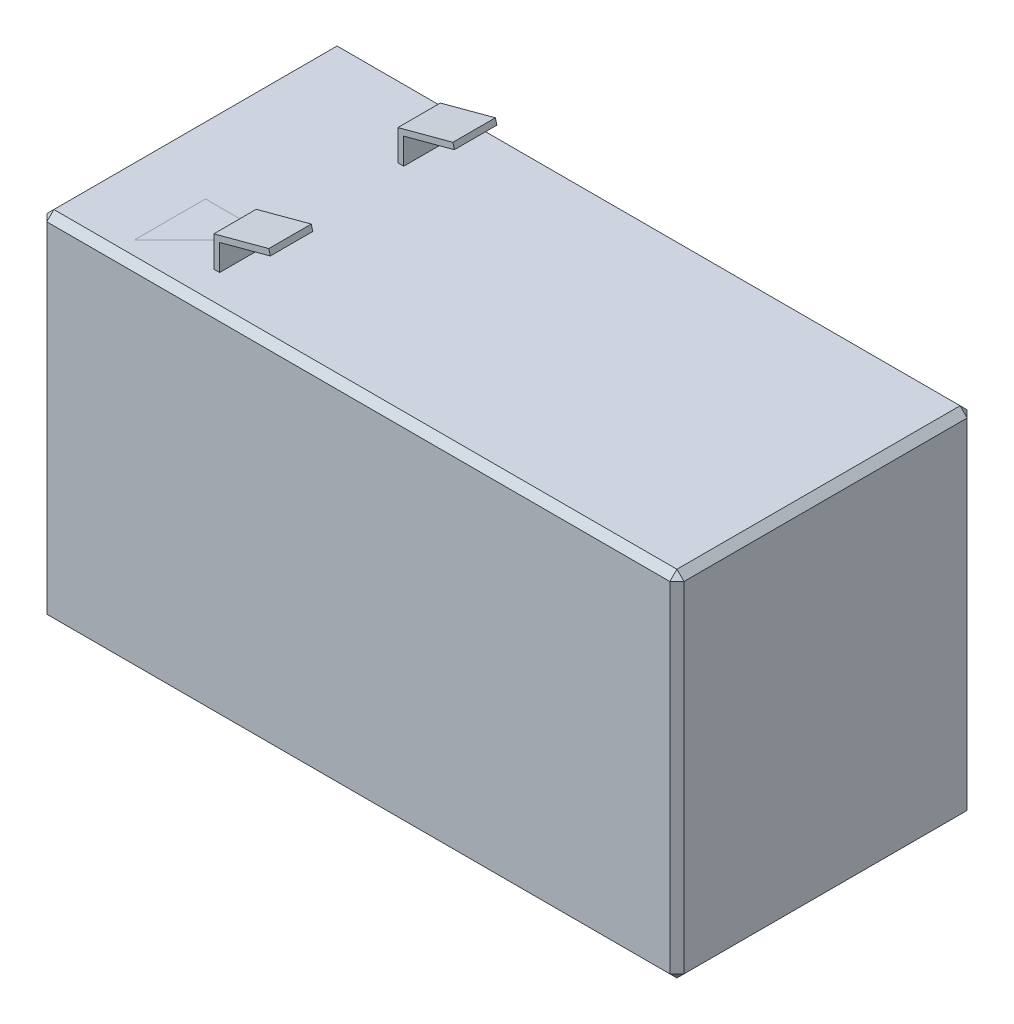
SolidWorks part; units mm, degrees
ref_plane "Plan de face" through (0, 0, 0) normal (0, 0, 1) x (1, 0, 0)
ref_plane "Plan de dessus" through (0, 0, 0) normal (0, 1, 0) x (1, 0, 0)
ref_plane "Plan de droite" through (0, 0, 0) normal (1, 0, 0) x (0, 0, -1)
sketch "Esquisse2" plane through (0, 0, 0) normal (0, 1, 0) x (1, 0, 0)
  line L1 (-45, -21) -> (45, -21)
  line L2 (-45, -21) -> (-45, 21)
  line L3 (-45, 21) -> (45, 21)
  line L4 (45, -21) -> (45, 21)
  line L5 (-45, -21) -> (45, 21) construction
  line L6 (-45, 21) -> (45, -21) construction
  point P0 (0, 0)
  dimension "D1" = 90
  dimension "D2" = 42
extrude "Boss.-Extru.1" add sketch "Esquisse2" along normal blind 50
ref_plane "Plan1" through (0, 0, 13) normal (0, 0, 1) x (1, 0, 0)
chamfer "Chanfrein1" distance 1 angle 45 12 edges at (-45, 0, 0) (-45, 50, 0) (45, 50, 0) (45, 25, -21) (0, 50, -21) (-45, 25, -21) (0, 0, -21) (45, 0, 0) (-45, 25, 21) (0, 50, 21) (45, 25, 21) (0, 0, 21)
sketch "Esquisse5" plane through (0, 0, 13) normal (0, 0, 1) x (1, 0, 0)
  line L0 (-25, 50) -> (-25, 54)
  line L1 (-44, 50) -> (44, 50) construction
  line L2 (-25, 54) -> (-17.5359, 56)
  line L3 (44, 0) -> (-44, 0) construction
  line L4 (-45, 1) -> (-45, 49) construction
  dimension "D1" = 56
  dimension "D2" = 15
  dimension "D3" = 20
  dimension "D4" = 4
extrude "Extru.-Mince1" add sketch "Esquisse5" along normal mid plane 6 thin thin type mid plane wall 0.83
mirror "Symétrie1" about plane through (0, 0, 0) normal (0, 0, 1) of "Extru.-Mince1"
sketch "Esquisse6" plane through (0, 50, 0) normal (0, 1, 0) x (1, 0, 0)
  line L0 (-70.3045, -13) -> (-86.9349, -13) construction
  line L1 (-24.585, -8) -> (-34.585, -8)
  line L2 (-24.585, -8) -> (-24.585, -18)
  line L3 (-24.585, -18) -> (-34.585, -18)
  line L4 (-34.585, -8) -> (-34.585, -18)
  line L5 (-27.5, -13) -> (27.5, -13) construction
  line L6 (-24.585, -16) -> (-24.585, -10) construction
  dimension "D1" = 10
surface "Surface-Plan1" sketch "Esquisse6"
sketch "Esquisse7" plane through (0, 50, 0) normal (0, 1, 0) x (1, 0, 0)
  line L0 (0, 0) -> (-17.4498, 0) construction
  line L1 (-24.585, -8) -> (-34.585, -8) construction
  line L2 (-34.585, -8) -> (-34.585, -18) construction
  line L3 (-24.585, -18) -> (-34.585, -18) construction
  line L4 (-24.585, -8) -> (-24.585, -18) construction
  line L5 (-24.585, -8) -> (-24.585, -18) construction
  line L6 (-24.585, -8) -> (-34.585, -8) construction
  line L7 (-34.585, -8) -> (-34.585, -18) construction
  line L8 (-24.585, -18) -> (-34.585, -18) construction
  line L9 (-24.585, 18) -> (-34.585, 18)
  line L10 (-34.585, 8) -> (-34.585, 18)
  line L11 (-24.585, 8) -> (-34.585, 8)
  line L12 (-24.585, 8) -> (-24.585, 18)
surface "Surface-Plan2" sketch "Esquisse7"
